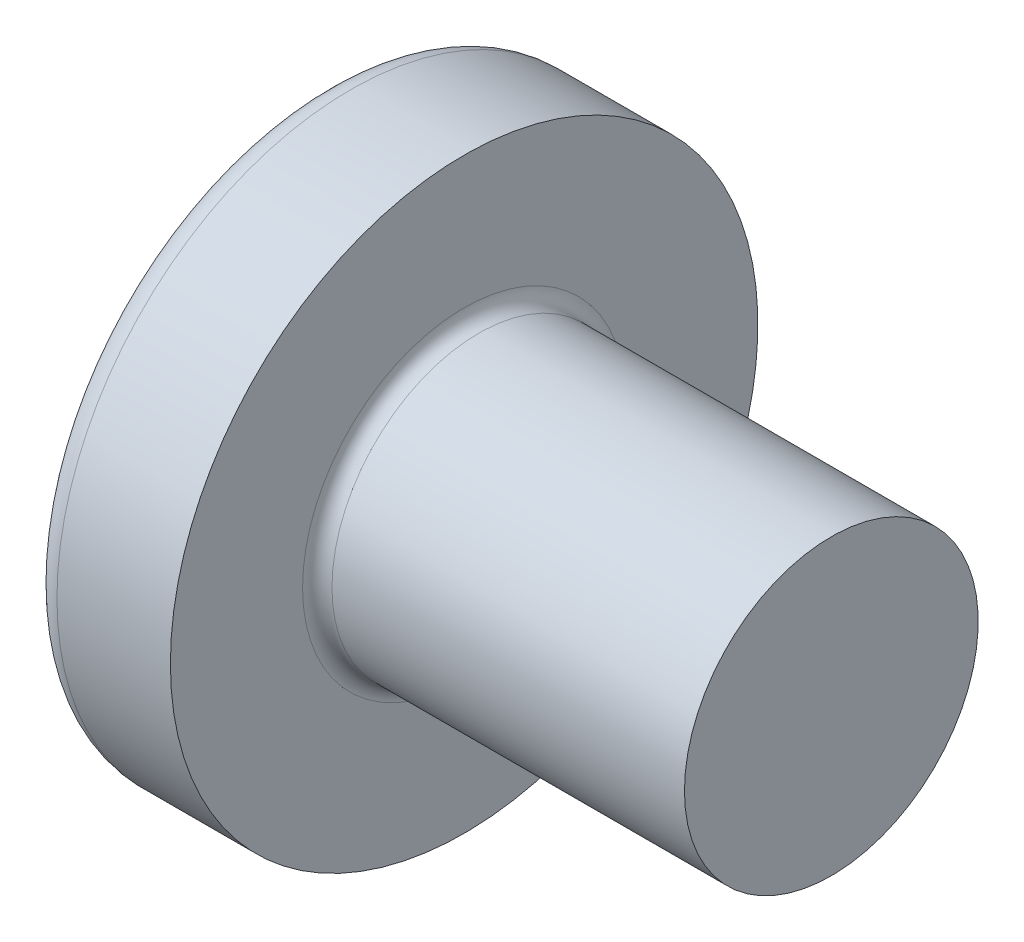
SolidWorks part; units mm, degrees
ref_plane "Plane1" through (0, 0, 0) normal (0, 0, 1) x (1, 0, 0)
ref_plane "Plane2" through (0, 0, 0) normal (0, 1, 0) x (1, 0, 0)
ref_plane "Plane3" through (0, 0, 0) normal (1, 0, 0) x (0, 0, -1)
sketch "BodySke" plane through (0, 0, 0) normal (0, 0, 1) x (1, 0, 0)
  line L0 (3.1, 2) -> (3.1, 4)
  line L1 (3.45, 6.35) -> (3.45, -3.175) construction
  line L2 (-25.4, 0) -> (127, 0) construction
  line L3 (8.1, 0) -> (0, 0)
  line L4 (3.1, 2) -> (8.1, 2)
  line L5 (8.1, 2) -> (8.1, 0)
  line L6 (1.5553, 4) -> (3.1, 4)
  line L8 (3.1, 6.35) -> (3.1, -3.175) construction
  arc A0 (1.2654, 3.8534) -> (0, 0) centre (6.5, 0) ccw
  arc A2 (1.2654, 3.8534) -> (1.5553, 4) centre (1.5553, 3.64) cw
revolve "Base-Revolve" add sketch "BodySke"
cosmetic thread "ThreadCosmetic" [suppressed]
fillet "Fillet1" radius 0.2 1 edges at (3.1, 0, 2)
sketch "Sketch3" plane through (0, 0, 0) normal (1, 0, 0) x (0, 0, -1)
  line L0 (0.515, -2.15) -> (-0.515, -2.15)
  line L1 (0.515, -2.15) -> (0.515, 2.15)
  line L2 (-0.515, 2.15) -> (0.515, 2.15)
  line L3 (-0.515, 2.15) -> (-0.515, -2.15)
  dimension "D1" = 1.3
  dimension "D2" = 0.37
ref_plane "Plane4" through (2.34, 0, 0) normal (1, 0, 0) x (0, 0, -1)
sketch "Sketch4" plane through (2.34, 0, 0) normal (1, 0, 0) x (0, 0, -1)
  line L0 (0.515, -0.9833) -> (-0.515, -0.9833)
  line L1 (0.515, -0.9833) -> (0.515, 0.9833)
  line L2 (-0.515, 0.9833) -> (0.515, 0.9833)
  line L3 (-0.515, 0.9833) -> (-0.515, -0.9833)
  dimension "D1" = 0.74
  dimension "D2" = 1.1043
  dimension "D3" = 0.37
  dimension "D4" = 0.5521
loft "Recess" cut profiles "Sketch3", "Sketch4"
pattern_circular "RecPat" count 2 every 90 about axis through (0, 0, 0) along (1, 0, 0) of "Recess"
sketch "RecCorSke" plane through (0, 0, 0) normal (0, 0, 1) x (1, 0, 0)
  line L0 (-3.175, 0) -> (15.875, 0) construction
  line L1 (-25.4, 0) -> (127, 0) construction
  line L2 (0, 0) -> (0, 1.0146)
  line L3 (0, 1.0146) -> (2.34, 0.851)
  line L4 (2.34, 0.851) -> (2.6165, 0)
  line L5 (2.6165, 0) -> (0, 0)
  dimension "Depth" = 1.5
  dimension "Draft_angle" = 4
  dimension "Bottom_angle" = 18
revolve "RecessCore" cut sketch "RecCorSke" angle 360 about L0
sketch "ThdSchSke" plane through (0, 0, 0) normal (0, 0, 1) x (1, 0, 0)
  line L0 (4.5, -1.61) -> (4.2269, -2)
  line L1 (4.5, -1.61) -> (4.7731, -2)
  line L2 (4.7731, -2) -> (4.7731, -2.5)
  line L3 (-3.175, 0) -> (5.1513, 0) construction
  line L5 (4.7731, -2.5) -> (4.2269, -2.5)
  line L6 (4.2269, -2.5) -> (4.2269, -2)
  dimension "SideAngle" = 55
  dimension "VeeAngle" = 70
  dimension "Thread_minor" = 1.993
  dimension "Overcut" = 3.125
  dimension "Diameter" = 2.5
  dimension "Start" = 3
revolve "ThreadSchematic" [suppressed] cut sketch "ThdSchSke" angle 360 about L3
pattern_linear "ThdSchPat" [suppressed]
equation "\"D1@Sketch3\" = \"Cross_dia@Sketch3\" / 2"
equation "\"D2@Sketch3\" = \"Cross_width@Sketch3\" / 2"
equation "\"Depth@RecCorSke\" = \"Cross_depth@Plane4\""
equation "\"D1@Sketch4\" = \"Cross_width@Sketch3\""
equation "\"D2@Sketch4\" = \"Cross_dia@Sketch3\" - 2.0 * \"Cross_depth@Plane4\" * tan(26.5  * 0.017453292)"
equation "\"D3@Sketch4\" = \"D1@Sketch4\" / 2"
equation "\"D4@Sketch4\" = \"D2@Sketch4\" / 2"
equation "\"Thread_length@ThreadCosmetic\" = ((sgn( (\"Length@BodySke\" - \"Advance@BodySke\" * 2.0 ) - \"Thread_nom@BodySke\" )-1)*( (\"Length@BodySke\" - \"Advance@BodySke\" * 2.0 ) - \"Thread_nom@BodySke\" ))/-2+ \"Thread_nom@BodySke\""
equation "\"Thread_minor@ThdSchSke\" = \"Thread_minor@ThreadCosmetic\""
equation "\"Diameter@ThdSchSke\" = \"Diameter@BodySke\""
equation "\"Overcut@ThdSchSke\" = \"Diameter@BodySke\" * 1.25"
equation "\"Start@ThdSchSke\" = \"Head_ht@BodySke\" + \"Length@BodySke\" - \"Thread_length@ThreadCosmetic\"  '---Non-countersunk---"
equation "\"Num_threads@ThdSchPat\" = int( \"Thread_length@ThreadCosmetic\" / \"Advance@BodySke\" + 0.999 )  + 1"
equation "\"Advance@ThdSchPat\" = \"Thread_length@ThreadCosmetic\" /  (\"Num_threads@ThdSchPat\" - 1) 'relax it"
